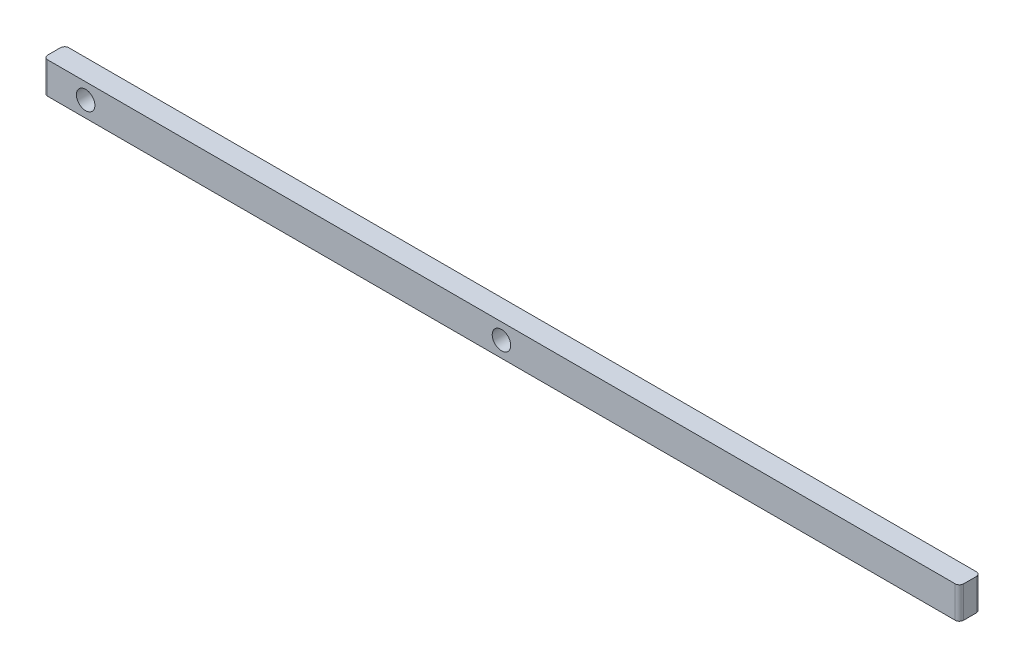
SolidWorks part; units mm, degrees
material "Balsa"
ref_plane "Front Plane" through (0, 0, 0) normal (0, 0, 1) x (1, 0, 0)
ref_plane "Top Plane" through (0, 0, 0) normal (0, 1, 0) x (1, 0, 0)
ref_plane "Right Plane" through (0, 0, 0) normal (1, 0, 0) x (0, 0, -1)
sketch "Sketch1" plane through (0, 0, 0) normal (0, 0, 1) x (1, 0, 0)
  line L1 (-276.225, -9.525) -> (276.225, -9.525)
  line L2 (-276.225, -9.525) -> (-276.225, 9.525)
  line L3 (-276.225, 9.525) -> (276.225, 9.525)
  line L4 (276.225, -9.525) -> (276.225, 9.525)
  line L5 (-276.225, -9.525) -> (276.225, 9.525) construction
  line L6 (-276.225, 9.525) -> (276.225, -9.525) construction
  point P0 (0, 0)
  dimension "D1" = 552.45
  dimension "D2" = 19.05
extrude "Boss-Extrude1" add sketch "Sketch1" along normal mid plane 12.7
sketch "Sketch2" plane through (0, 0, 6.35) normal (0, 0, 1) x (1, 0, 0)
  line L4 (276.225, -9.525) -> (276.225, 9.525)
  line L5 (276.225, 9.525) -> (-276.225, 9.525)
  line L6 (-276.225, 9.525) -> (-276.225, -9.525)
  line L7 (-276.225, -9.525) -> (276.225, -9.525)
  line L8 (276.225, -9.525) -> (276.225, 9.525)
  line L9 (276.225, 9.525) -> (-276.225, 9.525)
  line L10 (-276.225, 9.525) -> (-276.225, -9.525)
  line L11 (-276.225, -9.525) -> (276.225, -9.525)
  circle A0 centre (0, 0) radius 5.588
  circle A2 centre (-250.825, 0) radius 5.588
  point P11 (0, 0)
  point P12 (0, 0)
  point P13 (0, 0)
  dimension "D2" = 11.176
  dimension "D3" = 250.825
  dimension "D6" = 9.525
  dimension "D1" = 0
extrude "Cut-Extrude1" cut sketch "Sketch2" against normal through all both and the other way through all
fillet "Fillet1" radius 2.54 4 edges at (-276.225, 0, -6.35) (-276.225, 0, 6.35) (276.225, 0, -6.35) (276.225, 0, 6.35)
